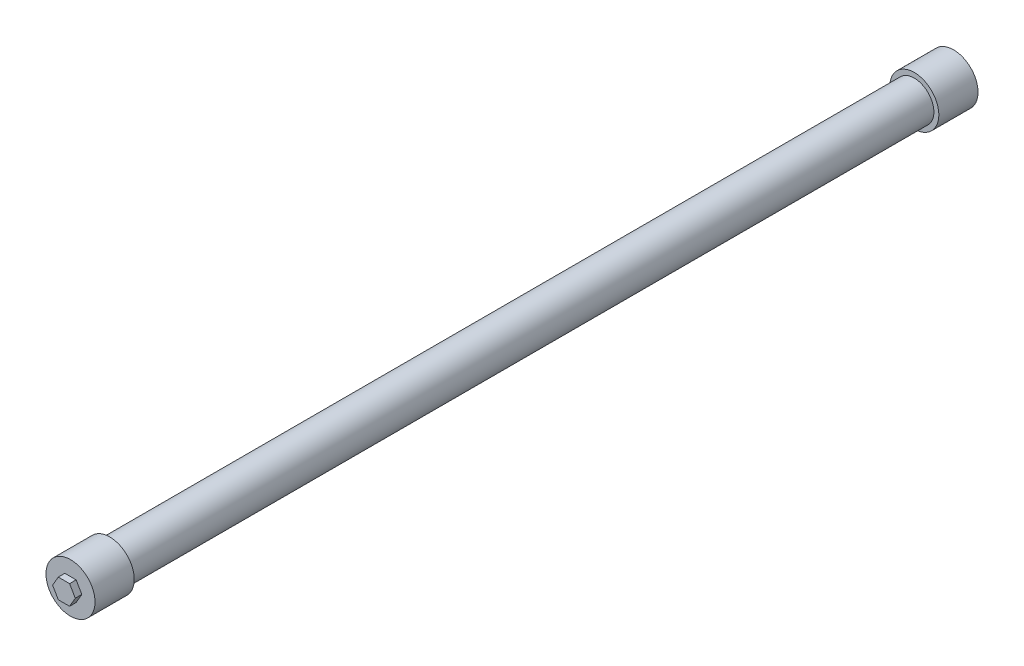
SolidWorks part; units mm, degrees
ref_plane "Alzado" through (0, 0, 0) normal (0, 0, 1) x (1, 0, 0)
ref_plane "Planta" through (0, 0, 0) normal (0, 1, 0) x (1, 0, 0)
ref_plane "Vista lateral" through (0, 0, 0) normal (1, 0, 0) x (0, 0, -1)
sketch "Croquis1" plane through (0, 0, 0) normal (0, 0, 1) x (1, 0, 0)
  circle A0 centre (0, 0) radius 6
extrude "Saliente-Extruir1" add sketch "Croquis1" along normal blind 250
sketch "Croquis2" plane through (0, 0, 250) normal (0, 0, 1) x (1, 0, 0)
  circle A0 centre (0, 0) radius 7.5
extrude "Saliente-Extruir2" add sketch "Croquis2" along normal blind 10 and the other way blind 2
sketch "Croquis3" plane through (0, 0, 0) normal (0, 0, -1) x (-1, 0, 0)
  circle A0 centre (0, 0) radius 7.5
extrude "Saliente-Extruir3" add sketch "Croquis3" along normal blind 10 and the other way blind 2
sketch "Croquis4" plane through (0, 0, 260) normal (0, 0, 1) x (1, 0, 0)
  line L1 (3.4641, 0) -> (1.7321, 3)
  line L2 (1.7321, 3) -> (-1.7321, 3)
  line L3 (-1.7321, 3) -> (-3.4641, 0)
  line L4 (-3.4641, 0) -> (-1.7321, -3)
  line L5 (-1.7321, -3) -> (1.7321, -3)
  line L6 (1.7321, -3) -> (3.4641, 0)
  circle A0 centre (0, 0) radius 3 construction
extrude "Saliente-Extruir4" add sketch "Croquis4" along normal blind 2
sketch "Croquis5" plane through (0, 0, -10) normal (0, 0, -1) x (-1, 0, 0)
  line L1 (1.9632, 2.8541) -> (-1.4901, 3.1272)
  line L2 (-1.4901, 3.1272) -> (-3.4533, 0.2731)
  line L3 (-3.4533, 0.2731) -> (-1.9632, -2.8541)
  line L4 (-1.9632, -2.8541) -> (1.4901, -3.1272)
  line L5 (1.4901, -3.1272) -> (3.4533, -0.2731)
  line L6 (3.4533, -0.2731) -> (1.9632, 2.8541)
  circle A0 centre (0, 0) radius 3 construction
extrude "Saliente-Extruir5" add sketch "Croquis5" along normal blind 2
